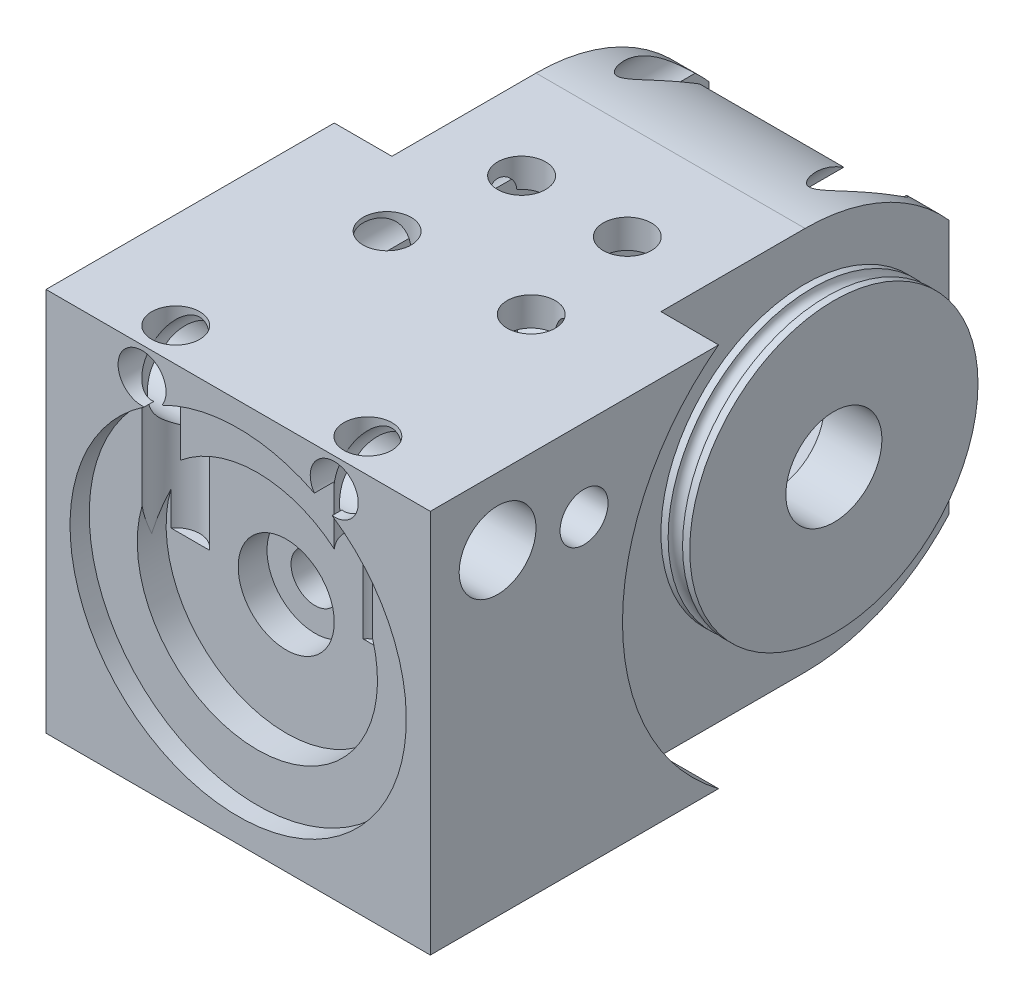
SolidWorks part; units mm, degrees
ref_plane "Alzado" through (0, 0, 0) normal (0, 0, 1) x (1, 0, 0)
ref_plane "Planta" through (0, 0, 0) normal (0, 1, 0) x (1, 0, 0)
ref_plane "Vista lateral" through (0, 0, 0) normal (1, 0, 0) x (0, 0, -1)
sketch "Croquis1" plane through (0, 0, 0) normal (0, 0, 1) x (1, 0, 0)
  line L1 (-20, -20) -> (20, -20)
  line L2 (-20, -20) -> (-20, 20)
  line L3 (-20, 20) -> (20, 20)
  line L4 (20, -20) -> (20, 20)
  line L5 (-20, -20) -> (20, 20) construction
  line L6 (-20, 20) -> (20, -20) construction
  point P0 (0, 0)
  dimension "D1" = 40
  dimension "D2" = 40
extrude "Saliente-Extruir1" add sketch "Croquis1" against normal blind 60
sketch "Croquis2" plane through (0, 0, 0) normal (0, 0, 1) x (1, 0, 0)
  circle A0 centre (0, 0) radius 17.5
  dimension "D1" = 35
extrude "Cortar-Extruir1" cut sketch "Croquis2" against normal blind 2
sketch "Croquis3" plane through (0, 0, -2) normal (0, 0, 1) x (1, 0, 0)
  circle A0 centre (0, 0) radius 12.5
  dimension "D1" = 25
extrude "Cortar-Extruir2" cut sketch "Croquis3" against normal blind 3
sketch "Croquis4" plane through (0, 0, -5) normal (0, 0, 1) x (1, 0, 0)
  circle A0 centre (0, 0) radius 5
  dimension "D1" = 10
extrude "Cortar-Extruir3" cut sketch "Croquis4" against normal blind 3
sketch "Croquis5" plane through (0, 0, -8) normal (0, 0, 1) x (1, 0, 0)
  circle A0 centre (0, 0) radius 2.5
  dimension "D1" = 5
extrude "Cortar-Extruir4" cut sketch "Croquis5" against normal through all
sketch "Croquis6" plane through (20, 0, 0) normal (1, 0, 0) x (0, 0, -1)
  line L0 (30, 20) -> (60, 20)
  line L1 (60, 20) -> (0, 20) construction
  line L2 (60, 20) -> (60, -20)
  line L3 (60, -20) -> (30, -20)
  line L4 (60, -20) -> (0, -20) construction
  arc A0 (30, -20) -> (30, 20) centre (45, 0) cw
  dimension "D1" = 15
  dimension "D2" = 25
extrude "Cortar-Extruir5" cut sketch "Croquis6" against normal blind 6
sketch "Croquis7" plane through (14, 0, 0) normal (1, 0, 0) x (0, 0, -1)
  circle A0 centre (45, 0) radius 15
  dimension "D1" = 30
extrude "Saliente-Extruir2" add sketch "Croquis7" along normal blind 3
sketch "Croquis9" plane through (-20, 0, 0) normal (-1, 0, 0) x (0, 0, 1)
  line L0 (-60, 20) -> (0, 20) construction
  line L1 (-30, 20) -> (-60, 20)
  line L3 (-30, -20) -> (-60, -20)
  line L4 (-60, 20) -> (-60, -20)
  arc A0 (-30, 20) -> (-30, -20) centre (-45, 0) cw
  dimension "D1" = 15
  dimension "D2" = 30
extrude "Cortar-Extruir6" cut sketch "Croquis9" against normal blind 6
sketch "Croquis10" plane through (-14, 0, 0) normal (-1, 0, 0) x (0, 0, 1)
  circle A0 centre (-45, 0) radius 15
  dimension "D1" = 30
extrude "Saliente-Extruir3" add sketch "Croquis10" along normal blind 3
sketch "Croquis12" plane through (14, 0, 0) normal (1, 0, 0) x (0, 0, -1)
  line L0 (45, 20) -> (60, 20)
  line L2 (60, 20) -> (60, 13.2288)
  line L5 (60, 0) -> (60, 20) construction
  line L6 (45, -20) -> (60, -20)
  line L8 (60, -20) -> (60, -13.2288)
  line L10 (60, 20) -> (30, 20) construction
  arc A0 (45, 20) -> (60, 13.2288) centre (45, 0) cw
  arc A1 (45, -20) -> (60, -13.2288) centre (45, 0) ccw
  dimension "D1" = 20
  dimension "D2" = 20
extrude "Cortar-Extruir7" cut sketch "Croquis12" against normal through all
sketch "Croquis13" plane through (17, 0, 0) normal (1, 0, 0) x (0, 0, -1)
  circle A0 centre (45, 0) radius 5
  dimension "D1" = 10
extrude "Cortar-Extruir8" cut sketch "Croquis13" against normal through all
ref_axis "Eje1" through (-17, 0, -45) along (1, 0, 0)
ref_plane "Plano2" through (0, 0, -45) normal (0, 0, 1) x (1, 0, 0)
sketch "Croquis14" plane through (0, 0, -45) normal (0, 0, 1) x (1, 0, 0)
  line L0 (17, 15) -> (14, 15) construction
  line L1 (-14, 15) -> (-17, 15) construction
  circle A0 centre (15.5, 15) radius 0.75
  circle A1 centre (-15.5, 15) radius 0.75
  dimension "D1" = 1.5
  dimension "D2" = 1.5
revolve "Cortar-Revolución1" cut sketch "Croquis14" angle 360 about axis through (-17, 0, -45) along (1, 0, 0)
sketch "Croquis15" plane through (0, 0, -60) normal (0, 0, -1) x (-1, 0, 0)
  line L1 (-11, -10.2288) -> (11, -10.2288)
  line L2 (-11, -10.2288) -> (-11, 17)
  line L3 (-11, 17) -> (11, 17)
  line L4 (11, -10.2288) -> (11, 17)
  line L5 (14, -13.2288) -> (-14, -13.2288) construction
  line L6 (14, 13.2288) -> (14, 0) construction
  line L7 (-14, 0) -> (-14, 13.2288) construction
  line L8 (14, 20) -> (-14, 20) construction
  dimension "D1" = 3
  dimension "D2" = 3
  dimension "D3" = 3
  dimension "D4" = 3
extrude "Cortar-Extruir9" cut sketch "Croquis15" against normal blind 40
sketch "Croquis16" plane through (-20, 0, 0) normal (-1, 0, 0) x (0, 0, 1)
  line L0 (0, 20) -> (0, -20) construction
  line L1 (-30, 20) -> (0, 20) construction
  circle A0 centre (-7, 13) radius 4
  dimension "D1" = 8
  dimension "D2" = 7
  dimension "D3" = 7
extrude "Cortar-Extruir10" cut sketch "Croquis16" against normal through all
sketch "Croquis17" plane through (0, 20, 0) normal (0, 1, 0) x (1, 0, 0)
  line L0 (-20, 30) -> (-20, 0) construction
  line L1 (20, 30) -> (20, 0) construction
  line L2 (20, 0) -> (-20, 0) construction
  circle A0 centre (10, 3.5) radius 2.5
  circle A1 centre (-10, 3.5) radius 2.5
  dimension "D1" = 5
  dimension "D2" = 5
  dimension "D3" = 10
  dimension "D4" = 10
  dimension "D5" = 3.5
  dimension "D6" = 3.5
extrude "Cortar-Extruir11" cut sketch "Croquis17" against normal blind 20
sketch "Croquis19" plane through (0, 0, -60) normal (0, 0, -1) x (-1, 0, 0)
  line L0 (-20, 20) -> (-20, -20) construction
  line L1 (20, -20) -> (20, 20) construction
  line L2 (14, 20) -> (-14, 20) construction
  circle A0 centre (-10, 17) radius 2.5
  circle A1 centre (10, 17) radius 2.5
  dimension "D1" = 5
  dimension "D2" = 5
  dimension "D3" = 10
  dimension "D4" = 10
  dimension "D5" = 3
  dimension "D6" = 3
extrude "Cortar-Extruir13" cut sketch "Croquis19" against normal through all
sketch "Croquis20" plane through (0, 20, 0) normal (0, 1, 0) x (1, 0, 0)
  line L0 (-20, 30) -> (-20, 0) construction
  line L1 (20, 30) -> (20, 0) construction
  line L2 (20, 0) -> (-20, 0) construction
  circle A0 centre (5.5, 35) radius 2.5
  circle A1 centre (-5.5, 35) radius 2.5
  dimension "D1" = 5
  dimension "D2" = 5
  dimension "D3" = 14.5
  dimension "D4" = 14.5
  dimension "D5" = 35
  dimension "D6" = 35
extrude "Cortar-Extruir14" cut sketch "Croquis20" against normal through all
sketch "Croquis21" plane through (20, 0, 0) normal (1, 0, 0) x (0, 0, -1)
  line L0 (0, -20) -> (0, 20) construction
  line L1 (30, 20) -> (0, 20) construction
  circle A0 centre (16, 11.5) radius 2.5
  dimension "D1" = 5
  dimension "D2" = 16
  dimension "D3" = 8.5
extrude "Cortar-Extruir19" cut sketch "Croquis21" against normal through all
sketch "Croquis22" plane through (0, 20, 0) normal (0, 1, 0) x (1, 0, 0)
  line L0 (20, 30) -> (20, 0) construction
  line L1 (-20, 30) -> (-20, 0) construction
  line L2 (20, 0) -> (-20, 0) construction
  circle A0 centre (7.5, 23) radius 2.5
  circle A1 centre (-7.5, 23) radius 2.5
  dimension "D1" = 5
  dimension "D2" = 5
  dimension "D3" = 12.5
  dimension "D4" = 12.5
  dimension "D5" = 23
  dimension "D6" = 23
extrude "Cortar-Extruir20" cut sketch "Croquis22" against normal through all
